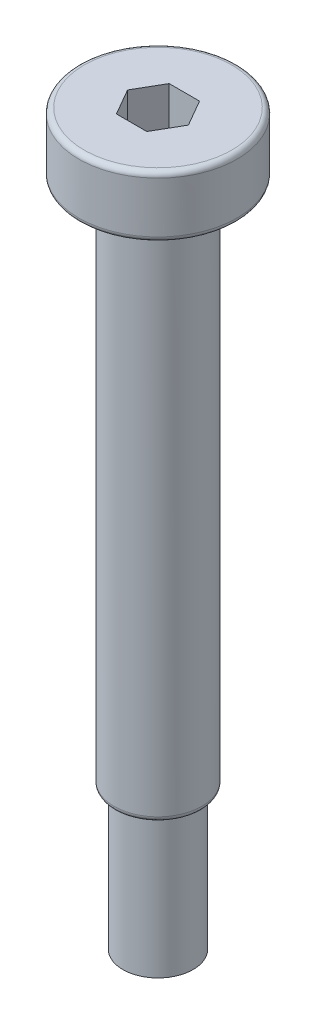
SolidWorks part; units mm, degrees
ref_plane "前视基准面" through (0, 0, 0) normal (0, 0, 1) x (1, 0, 0)
ref_plane "上视基准面" through (0, 0, 0) normal (0, 1, 0) x (1, 0, 0)
ref_plane "右视基准面" through (0, 0, 0) normal (1, 0, 0) x (0, 0, -1)
other "Configuration Table"
sketch "草图1" plane through (0, 0, 0) normal (0, 0, 1) x (1, 0, 0)
  line L0 (0, 0) -> (-2, 0)
  line L1 (-2, 0) -> (-2, 8)
  line L2 (-2, 8) -> (-2.5, 8)
  line L3 (-2.5, 8) -> (-2.5, 38)
  line L4 (-2.5, 38) -> (-4.5, 38)
  line L5 (-4.5, 38) -> (-4.5, 41.5)
  line L6 (-4.5, 41.5) -> (0, 41.5)
  line L7 (0, 41.5) -> (0, 0) construction
  line L8 (0, 0) -> (0, 41.5)
  dimension "D1" = 9
  dimension "D2" = 30
  dimension "D3" = 5
  dimension "D4" = 3.5
  dimension "D5" = 4
  dimension "D6" = 8
revolve "旋转1" add sketch "草图1" angle 360 about L7
cosmetic thread "装饰螺纹线1" parameters "D2"=3.242
fillet "圆角1" radius 0.3 3 edges at (-4.5, 41.5, 0) (-2.5, 8, 0) (-4.5, 38, 0)
sketch "草图2" plane through (0, 41.5, 0) normal (0, 1, 0) x (1, 0, 0)
  line L1 (0.866, -1.5) -> (1.7321, 0)
  line L2 (1.7321, 0) -> (0.866, 1.5)
  line L3 (0.866, 1.5) -> (-0.866, 1.5)
  line L4 (-0.866, 1.5) -> (-1.7321, 0)
  line L5 (-1.7321, 0) -> (-0.866, -1.5)
  line L6 (-0.866, -1.5) -> (0.866, -1.5)
  circle A0 centre (0, 0) radius 1.5 construction
  dimension "D1" = 3
extrude "切除-拉伸1" cut sketch "草图2" against normal blind 2.4
